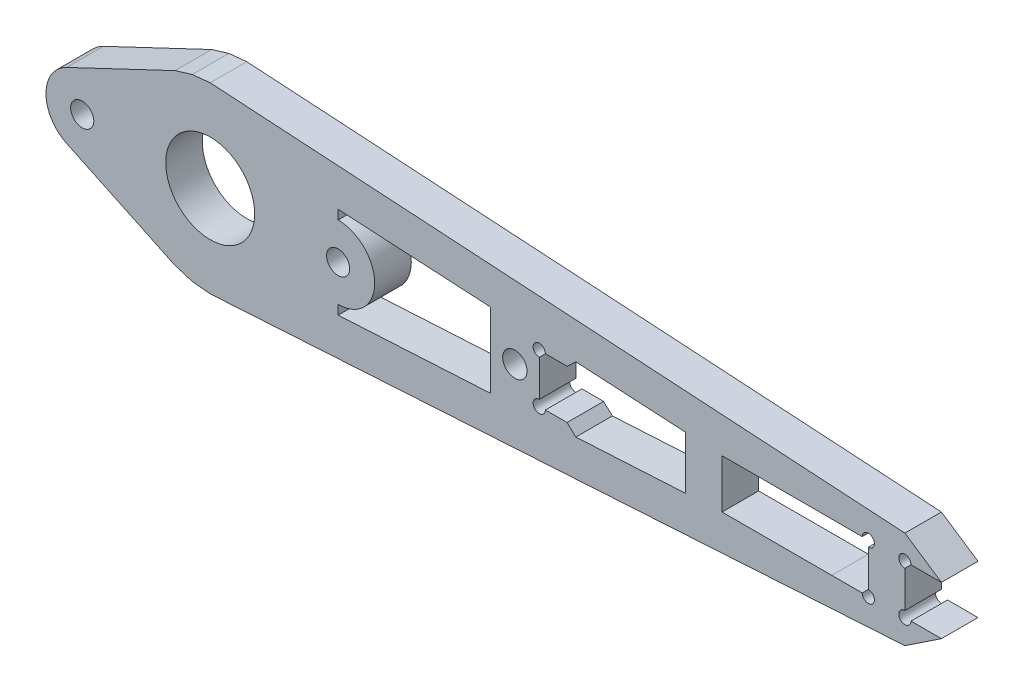
SolidWorks part; units mm, degrees
ref_plane "前视基准面" through (0, 0, 0) normal (0, 0, 1) x (1, 0, 0)
ref_plane "上视基准面" through (0, 0, 0) normal (0, 1, 0) x (1, 0, 0)
ref_plane "右视基准面" through (0, 0, 0) normal (1, 0, 0) x (0, 0, -1)
sketch "草图2" plane through (0, 0, 0) normal (0, 0, 1) x (1, 0, 0)
  line L0 (42, 2.0029) -> (51, 2)
  line L1 (51, 2) -> (53.5, 2)
  line L2 (42, -2.0029) -> (51, -2)
  line L3 (51, -2) -> (53.5, -2)
  line L4 (57, 4) -> (0, 7.5)
  line L5 (0, 7.5) -> (-1.4632, 7.3559)
  line L6 (-1.4632, 7.3559) -> (-2.8701, 6.9291)
  line L7 (-2.8701, 6.9291) -> (-11.763, 2.7105)
  line L8 (-11.763, -2.7105) -> (-2.8701, -6.9291)
  line L9 (-2.8701, -6.9291) -> (-1.4632, -7.3559)
  line L10 (-1.4632, -7.3559) -> (0, -7.5)
  line L11 (0, -7.5) -> (57, -4)
  line L12 (27.5, 2) -> (29.2826, 2)
  line L13 (27, -1.5) -> (27, 1.5)
  line L14 (29.2826, -2) -> (30, -2.6735)
  line L15 (30, -2.6735) -> (39, -2.1706)
  line L16 (39, 2.1706) -> (39, -2.1706)
  line L17 (30, 2.6735) -> (39, 2.1706)
  line L18 (30, 2.6735) -> (29.2826, 2)
  line L19 (10.5, -3.7632) -> (10.5, -3)
  line L20 (10.5, -3.7632) -> (23, -3.0647)
  line L21 (23, 3.0647) -> (23, -3.0647)
  line L22 (10.5, 3.7632) -> (23, 3.0647)
  line L23 (10.5, 3.7632) -> (10.5, 3)
  line L30 (42, -2.0029) -> (42, 2.0029)
  line L31 (54, 1.5) -> (54, -1.5)
  line L32 (57, -4) -> (60, -2)
  line L33 (57, -1.5) -> (57, 1.5)
  line L34 (57, 4) -> (60, 2)
  line L35 (57.5, -2) -> (60, -2)
  line L36 (60, 2) -> (57.5, 2)
  line L37 (29.2826, -2) -> (27.5, -2)
  circle A0 centre (25, 0) radius 1
  circle A1 centre (10.5, 0) radius 0.95
  circle A2 centre (-10.5, 0) radius 0.95
  arc A3 (-11.763, 2.7105) -> (-11.763, -2.7105) centre (-10.4772, 0) ccw
  arc A4 (27.5, 2) -> (27, 1.5) centre (27, 2) ccw
  arc A5 (27, -1.5) -> (27.5, -2) centre (27, -2) ccw
  arc A6 (10.5, -3) -> (10.5, 3) centre (10.5, 0) ccw
  arc A7 (53.5, -2) -> (54, -1.5) centre (54, -2) ccw
  arc A8 (54, 1.5) -> (53.5, 2) centre (54, 2) ccw
  arc A9 (57, -1.5) -> (57.5, -2) centre (57, -2) ccw
  arc A10 (57.5, 2) -> (57, 1.5) centre (57, 2) ccw
  circle A11 centre (0, 0) radius 3.65
  dimension "D1" = 1.9
  dimension "D3" = 1.9
  dimension "D4" = 7.3
  dimension "D5" = 2
  dimension "D2" = 6.1293
extrude "凸台-拉伸2" add sketch "草图2" along normal blind 3
